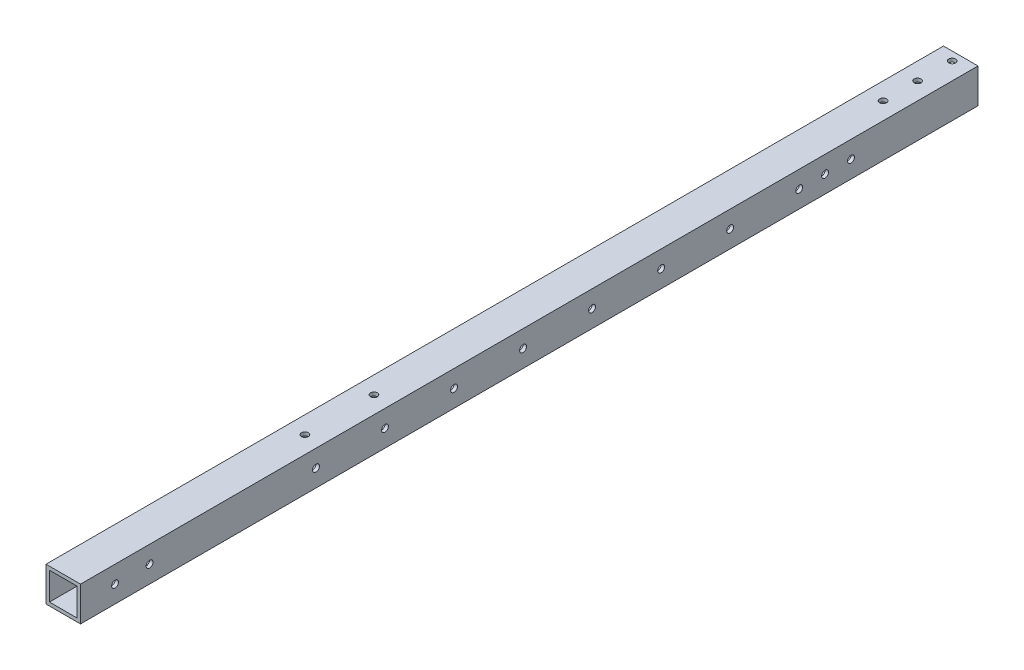
SolidWorks part; units mm, degrees
ref_plane "前视基准面" through (0, 0, 0) normal (0, 0, 1) x (1, 0, 0)
ref_plane "上视基准面" through (0, 0, 0) normal (0, 1, 0) x (1, 0, 0)
ref_plane "右视基准面" through (0, 0, 0) normal (1, 0, 0) x (0, 0, -1)
sketch "草图1" plane through (0, 0, 0) normal (0, 0, 1) x (1, 0, 0)
  line L1 (-10, 10) -> (10, 10)
  line L2 (-10, 10) -> (-10, -10)
  line L3 (-10, -10) -> (10, -10)
  line L4 (10, 10) -> (10, -10)
  line L5 (-10, 10) -> (10, -10) construction
  line L6 (-10, -10) -> (10, 10) construction
  line L7 (-8, 8) -> (8, 8)
  line L8 (-8, 8) -> (-8, -8)
  line L9 (-8, -8) -> (8, -8)
  line L10 (8, 8) -> (8, -8)
  line L11 (-8, 8) -> (8, -8) construction
  line L12 (-8, -8) -> (8, 8) construction
  point P0 (0, 0)
  point P5 (0, 0)
  dimension "D1" = 20
  dimension "D2" = 16
extrude "凸台-拉伸1" add sketch "草图1" along normal blind 520
sketch "草图2" plane through (0, -10, 0) normal (0, -1, 0) x (1, 0, 0)
  circle A0 centre (0, 5) radius 2 construction
  circle A1 centre (0, 25) radius 2 construction
  circle A2 centre (0, 45) radius 2 construction
  circle A3 centre (0, 5) radius 2
  circle A4 centre (0, 25) radius 2
  circle A5 centre (0, 45) radius 2
extrude "切除-拉伸1" cut sketch "草图2" against normal through all
sketch "草图3" plane through (10, 0, 0) normal (1, 0, 0) x (0, 0, -1)
  line L0 (-1000, 0) -> (49000, 0) construction
  line L1 (0, -10) -> (0, 10) construction
  line L2 (-520, -10) -> (-520, 10) construction
  circle A0 centre (-500, 0) radius 2
  circle A1 centre (-480, 0) radius 2
  point P5 (0, 0)
  dimension "D1" = 4
  dimension "D2" = 4
  dimension "D3" = 20
  dimension "D4" = 40
extrude "切除-拉伸2" cut sketch "草图3" against normal through all
sketch "草图4" plane through (10, 0, 0) normal (1, 0, 0) x (0, 0, -1)
  line L0 (-103.5898, 0) -> (-143.5898, 0) construction
  circle A0 centre (-103.5898, 0) radius 2 construction
  circle A1 centre (-88.5898, 0) radius 2 construction
  circle A2 centre (-73.5898, 0) radius 2 construction
  circle A3 centre (-103.5898, 0) radius 2
  circle A4 centre (-88.5898, 0) radius 2
  circle A5 centre (-73.5898, 0) radius 2
  circle A6 centre (-143.5898, 0) radius 2
  circle A7 centre (-183.5898, 0) radius 2
  circle A8 centre (-223.5898, 0) radius 2
  circle A9 centre (-263.5898, 0) radius 2
  circle A10 centre (-303.5898, 0) radius 2
  circle A11 centre (-343.5898, 0) radius 2
  circle A12 centre (-383.5898, 0) radius 2
  dimension "D2" = 40
  dimension "D1" = 8
extrude "切除-拉伸3" cut sketch "草图4" against normal through all
sketch "草图5" plane through (0, -10, 0) normal (0, -1, 0) x (1, 0, 0)
  line L0 (0, 546.7098) -> (0, -24.6984) construction
  line L1 (-10, 520) -> (10, 520) construction
  circle A0 centre (0, 380) radius 2
  circle A1 centre (0, 340) radius 2
  dimension "D1" = 4
  dimension "D2" = 4
  dimension "D3" = 40
  dimension "D4" = 140
extrude "切除-拉伸4" cut sketch "草图5" against normal through all
